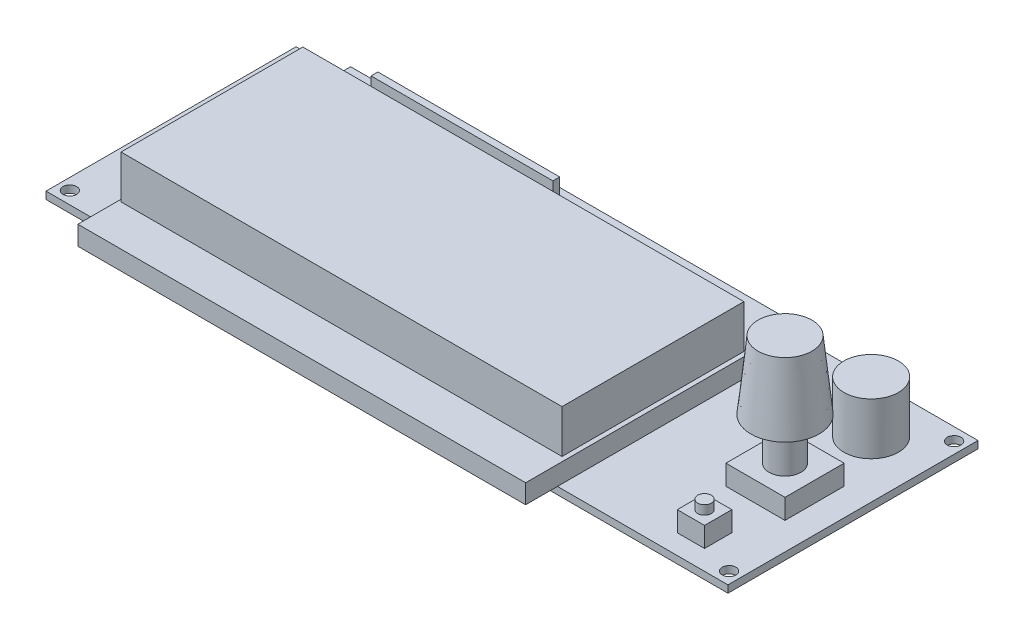
SolidWorks part; units mm, degrees
ref_plane "Front Plane" through (0, 0, 0) normal (0, 0, 1) x (1, 0, 0)
ref_plane "Top Plane" through (0, 0, 0) normal (0, 1, 0) x (1, 0, 0)
ref_plane "Right Plane" through (0, 0, 0) normal (1, 0, 0) x (0, 0, -1)
sketch "Sketch1" plane through (0, 0, 0) normal (0, 1, 0) x (1, 0, 0)
  line L1 (-75, -27.5) -> (75, -27.5)
  line L2 (-75, -27.5) -> (-75, 27.5)
  line L3 (-75, 27.5) -> (75, 27.5)
  line L4 (75, -27.5) -> (75, 27.5)
  line L5 (-75, -27.5) -> (75, 27.5) construction
  line L6 (-75, 27.5) -> (75, -27.5) construction
  point P0 (0, 0)
  dimension "D1" = 150
  dimension "D2" = 55
extrude "MainPCB" add sketch "Sketch1" along normal blind 1.6
sketch "Sketch2" plane through (0, 1.6, 0) normal (0, 1, 0) x (1, 0, 0)
  line L0 (0, 27.5) -> (0, -27.5) construction
  line L1 (75, 27.5) -> (-75, 27.5) construction
  line L2 (-75, -27.5) -> (75, -27.5) construction
  line L3 (75, 0) -> (-75, 0) construction
  line L4 (-75, 27.5) -> (-75, -27.5) construction
  line L5 (-72.5, -24.75) -> (-72.5, 24.75) construction
  line L6 (72.5, -24.75) -> (72.5, 24.75) construction
  circle A0 centre (-72.5, 24.75) radius 1.5
  circle A1 centre (-72.5, -24.75) radius 1.5
  circle A2 centre (72.5, -24.75) radius 1.5
  circle A3 centre (72.5, 24.75) radius 1.5
  point P15 (-72.5, 0)
  point P17 (0, 0)
  point P21 (72.5, 0)
  dimension "D1" = 3
  dimension "D2" = 24.75
  dimension "D3" = 72.5
extrude "ScrewHoles" cut sketch "Sketch2" against normal through all
sketch "Sketch3" plane through (0, 1.6, 0) normal (0, 1, 0) x (1, 0, 0)
  line L0 (75, 27.5) -> (-75, 27.5) construction
  line L1 (-61, 25.5) -> (37.5, 25.5)
  line L2 (-61, 25.5) -> (-61, -34.5)
  line L3 (-61, -34.5) -> (37.5, -34.5)
  line L4 (37.5, 25.5) -> (37.5, -34.5)
  line L5 (-61, 25.5) -> (37.5, -34.5) construction
  line L6 (-61, -34.5) -> (37.5, 25.5) construction
  line L7 (-75, 27.5) -> (-75, -27.5) construction
  dimension "D1" = 98.5
  dimension "D2" = 60
  dimension "D3" = 2
  dimension "D4" = 14
extrude "Boss-Extrude2" add sketch "Sketch3" along normal blind 4.2
sketch "Sketch4" plane through (0, 5.8, 0) normal (0, 1, 0) x (1, 0, 0)
  line L0 (37.5, -27.5) -> (75, -27.5) construction
  line L1 (-60.5, 14.5) -> (36.5, 14.5)
  line L2 (-60.5, 14.5) -> (-60.5, -25.5)
  line L3 (-60.5, -25.5) -> (36.5, -25.5)
  line L4 (36.5, 14.5) -> (36.5, -25.5)
  line L5 (-60.5, 14.5) -> (36.5, -25.5) construction
  line L6 (-60.5, -25.5) -> (36.5, 14.5) construction
  line L7 (-75, 27.5) -> (-75, -27.5) construction
  point P0 (-12, -5.5)
  point P5 (-46.8516, 21.7997)
  point P8 (-75, 0)
  dimension "D1" = 97
  dimension "D2" = 40
  dimension "D3" = 2
  dimension "D4" = 14.5
extrude "Boss-Extrude3" add sketch "Sketch4" along normal blind 9.5
sketch "Sketch5" plane through (0, 1.6, 0) normal (0, 1, 0) x (1, 0, 0)
  line L0 (62.5, 27.5) -> (62.5, -27.5) construction
  line L1 (75, 27.5) -> (-75, 27.5) construction
  line L3 (37.5, -27.5) -> (75, -27.5) construction
  line L5 (56, 4.05) -> (69, 4.05)
  line L6 (56, 4.05) -> (56, -8.95)
  line L7 (56, -8.95) -> (69, -8.95)
  line L8 (69, 4.05) -> (69, -8.95)
  line L9 (56, 4.05) -> (69, -8.95) construction
  line L10 (56, -8.95) -> (69, 4.05) construction
  line L11 (59.5, -17.15) -> (65.5, -17.15)
  line L12 (59.5, -17.15) -> (59.5, -23.15)
  line L13 (59.5, -23.15) -> (65.5, -23.15)
  line L14 (65.5, -17.15) -> (65.5, -23.15)
  line L15 (59.5, -17.15) -> (65.5, -23.15) construction
  line L16 (59.5, -23.15) -> (65.5, -17.15) construction
  circle A0 centre (72.5, -24.75) radius 1.5 construction
  circle A1 centre (62.5, 16.5) radius 6
  point P8 (62.5, -20.15)
  point P11 (62.5, -2.45)
  dimension "D1" = 10
  dimension "D2" = 12
  dimension "D3" = 11
  dimension "D4" = 6
  dimension "D5" = 6
  dimension "D6" = 1.6
  dimension "D7" = 13
  dimension "D8" = 13
  dimension "D9" = 22.3
extrude "Boss-Extrude4" add sketch "Sketch5" along normal blind 4.4
sketch "Sketch6" plane through (0, 6, 0) normal (0, 1, 0) x (1, 0, 0)
  line L0 (62.5, -17.15) -> (62.5, -23.15) construction
  line L1 (65.5, -17.15) -> (59.5, -17.15) construction
  line L2 (59.5, -23.15) -> (65.5, -23.15) construction
  circle A0 centre (62.5, -20.15) radius 1.5
  dimension "D1" = 3
extrude "Boss-Extrude5" add sketch "Sketch6" along normal blind 2
sketch "Sketch7" plane through (0, 6, 0) normal (0, 1, 0) x (1, 0, 0)
  circle A0 centre (62.5, 16.5) radius 6
  circle A1 centre (62.5, 16.5) radius 6 construction
extrude "Boss-Extrude6" add sketch "Sketch7" along normal blind 7
sketch "Sketch8" plane through (0, 6, 0) normal (0, 1, 0) x (1, 0, 0)
  line L0 (62.5, 4.05) -> (62.5, -8.95) construction
  line L1 (69, 4.05) -> (56, 4.05) construction
  line L2 (56, -8.95) -> (69, -8.95) construction
  circle A0 centre (62.5, -2.45) radius 3.5
  dimension "D1" = 7
extrude "Boss-Extrude7" add sketch "Sketch8" along normal up to surface (9.3 mm away) up to face at (-12, 15.3, 5.5)
sketch "Sketch9" plane through (0, 15.3, 0) normal (0, 1, 0) x (1, 0, 0)
  circle A0 centre (62.5, -2.45) radius 7.5
  circle A3 centre (62.5, -2.45) radius 3.5 construction
  dimension "D1" = 15
extrude "Boss-Extrude8" add sketch "Sketch9" along normal blind 15 draft 6
sketch "Sketch10" plane through (0, 5.8, 0) normal (0, 1, 0) x (1, 0, 0)
  line L0 (-75, 27.5) -> (-75, -27.5) construction
  line L1 (-52, 22.5) -> (-12, 22.5)
  line L2 (-52, 22.5) -> (-52, 21)
  line L3 (-52, 21) -> (-12, 21)
  line L4 (-12, 22.5) -> (-12, 21)
  line L5 (-52, 22.5) -> (-12, 21) construction
  line L6 (-52, 21) -> (-12, 22.5) construction
  line L8 (75, 27.5) -> (-75, 27.5) construction
  point P0 (-32, 21.75)
  dimension "D1" = 1.5
  dimension "D2" = 40
  dimension "D3" = 23
  dimension "D4" = 6.5
extrude "AnnoyinglyPlacedPins" add sketch "Sketch10" along normal blind 5
